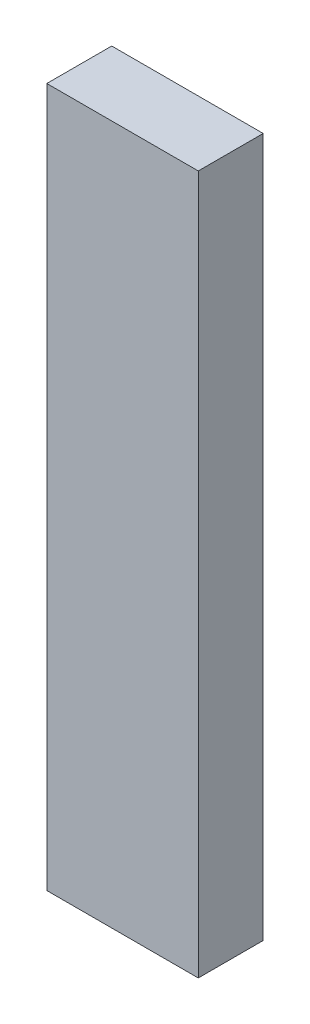
SolidWorks part; units mm, degrees
ref_plane "Front Plane" through (0, 0, 0) normal (0, 0, 1) x (1, 0, 0)
ref_plane "Top Plane" through (0, 0, 0) normal (0, 1, 0) x (1, 0, 0)
ref_plane "Right Plane" through (0, 0, 0) normal (1, 0, 0) x (0, 0, -1)
sketch "Sketch1" plane through (0, 0, 0) normal (0, 0, 1) x (1, 0, 0)
  line L1 (-3.5, 16.15) -> (3.5, 16.15)
  line L2 (-3.5, 16.15) -> (-3.5, -16.15)
  line L3 (-3.5, -16.15) -> (3.5, -16.15)
  line L4 (3.5, 16.15) -> (3.5, -16.15)
  line L5 (-3.5, 16.15) -> (3.5, -16.15) construction
  line L6 (-3.5, -16.15) -> (3.5, 16.15) construction
  point P0 (0, 0)
  dimension "D1" = 7
  dimension "D2" = 32.3
extrude "Boss-Extrude1" add sketch "Sketch1" along normal blind 3
